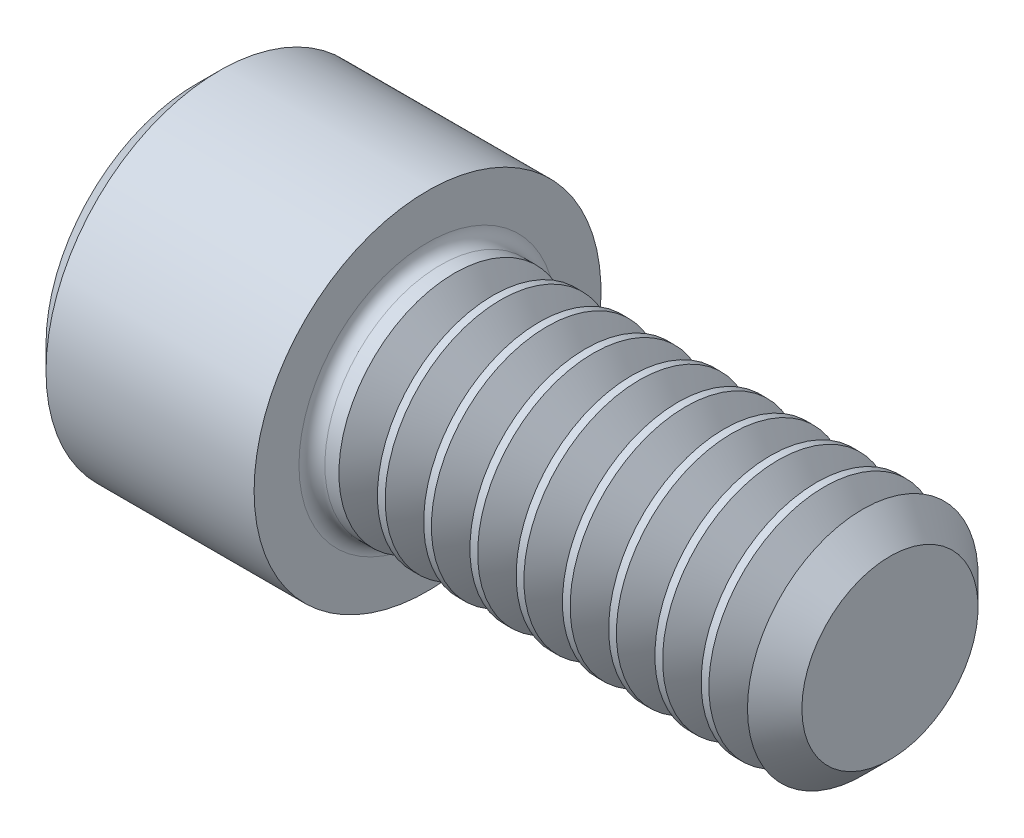
SolidWorks part; units mm, degrees
revolve "Base-Revolve" add sketch "BodySke"
sketch "BodySke" plane through (0, 0, 0) normal (0, 0, 1) x (1, 0, 0)
  line L0 (0, 0) -> (0, 4.1275)
  line L1 (0.635, 4.7625) -> (6.35, 4.7625)
  line L2 (6.35, 4.7625) -> (6.35, 3.175)
  line L3 (6.35, 3.175) -> (18.2944, 3.175)
  line L4 (19.05, 2.4193) -> (19.05, 0)
  line L5 (19.05, 0) -> (0, 0)
  line L6 (-31.75, 0) -> (127, 0) construction
  line L7 (0, 4.1275) -> (0.635, 4.7625)
  line L8 (19.05, 2.4193) -> (18.2944, 3.175)
  line L9 (0, -4.1275) -> (0.635, -4.7625) construction
  line L10 (19.05, -2.4193) -> (18.2944, -3.175) construction
  line L11 (7.62, 9.525) -> (7.62, 3.175) construction
  line L12 (6.35, 9.525) -> (6.35, 3.175) construction
  line L13 (-19.05, 9.525) -> (-19.05, 3.175) construction
  dimension "Diameter" = 6.35
  dimension "Head_ht" = 6.35
  dimension "Length" = 12.7
  dimension "Body_ch_ang" = 45
  dimension "Head_dia" = 9.525
  dimension "Head_ch_ang" = 45
  dimension "Head_side_ht" = 5.715
  dimension "Minor_dia" = 4.8387
  dimension "Advance" = 1.27
  dimension "Thread_nom" = 12.7
  dimension "Thread_length" = 38.1
cosmetic thread "ThreadCosmetic" [suppressed]
fillet "Fillet1" radius 0.3556 1 edges at (6.35, 0, 3.175)
ref_plane "Plane1" through (0, 0, 0) normal (0, 0, 1) x (1, 0, 0)
ref_plane "Plane2" through (0, 0, 0) normal (0, 1, 0) x (1, 0, 0)
ref_plane "Plane3" through (0, 0, 0) normal (1, 0, 0) x (0, 0, -1)
other "Configuration Table"
sketch "Sketch2" plane through (0, 0, 0) normal (0, 0, 1) x (1, 0, 0)
  line L0 (0, 2.3813) -> (3.048, 2.3813)
  line L1 (3.048, 2.3813) -> (4.4228, 0)
  line L2 (-31.75, 0) -> (127, 0) construction
  line L3 (4.4228, 0) -> (0, 0)
  line L4 (0, 0) -> (0, 2.3813)
  line L5 (0, 4.1275) -> (0, -4.1275) construction
  line L6 (0, 0) -> (47.625, 0) construction
  line L7 (6.35, -4.7625) -> (6.35, 4.7625) construction
  dimension "D1" = 2.3813
  dimension "D2" = 60
revolve "Hex-PreBroach" cut sketch "Sketch2" angle 360 about L6
sketch "Sketch3" plane through (0, 0, 0) normal (-1, 0, 0) x (0, 0.5, 0.866)
  line L0 (1.3748, 2.3813) -> (-1.3748, 2.3812)
  line L1 (-1.3748, 2.3812) -> (-2.7496, 0)
  line L2 (1.3748, 2.3813) -> (2.7496, 0)
  line L3 (1.3748, -2.3812) -> (2.7496, 0)
  line L4 (1.3748, -2.3812) -> (-1.3748, -2.3812)
  line L5 (-1.3748, -2.3812) -> (-2.7496, 0)
  dimension "D1" = 2.3813
  dimension "D2" = 2.3813
  dimension "Hex_size" = 4.7625
extrude "Hex" cut sketch "Sketch3" against normal blind 3.048
sketch "Sketch4" plane through (0, 0, 0) normal (-1, 0, 0) x (0, 0, 1)
  line L0 (0, 0) -> (2.8067, 0)
  line L1 (0, 0) -> (6.1484, 3.5498) construction
  line L2 (0, 0) -> (1.4033, 2.4307)
  line L3 (2.3336, 0.614) -> (2.6851, 0.817)
  line L4 (1.6986, 1.7139) -> (2.0501, 1.9169)
  arc A0 (2.3336, 0.614) -> (1.6986, 1.7139) centre (0, 0) ccw
  arc A1 (2.8067, 0) -> (2.6851, 0.817) centre (0, 0) ccw
  arc A2 (1.4033, 2.4307) -> (2.0501, 1.9169) centre (0, 0) cw
  dimension "D2" = 60
  dimension "D1" = 30
  dimension "Spline_p_dim" = 1.27
  dimension "D3" = 0.635
extrude "Spline" [suppressed] cut sketch "Sketch4" against normal blind 3.048
pattern_circular "CirPattern1" [suppressed] count 6 every 60
sketch "Sketch5" plane through (0, 0, 0) normal (0, 0, 1) x (1, 0, 0)
  line L0 (-31.75, 0) -> (127, 0) construction
  line L2 (0, 4.1275) -> (0, -4.1275) construction
  circle A0 centre (2.159, 0) radius 0.5905
  dimension "Drilled_hole_dia" = 1.1811
  dimension "Drilled_hole_loc" = 2.159
extrude "Hole" [suppressed] cut sketch "Sketch5" against normal through all and the other way through all
pattern_circular "Drilled-4" [suppressed] count 2 every 60
pattern_circular "Drilled-6" [suppressed] count 3 every 60
sketch "ThdSchSke" plane through (0, 0, 0) normal (0, 0, 1) x (1, 0, 0)
  line L0 (7.62, -2.4193) -> (7.0909, -3.175)
  line L1 (7.62, -2.4193) -> (8.1491, -3.175)
  line L2 (8.1491, -3.175) -> (8.1491, -3.9688)
  line L3 (-3.175, 0) -> (5.1513, 0) construction
  line L5 (8.1491, -3.9688) -> (7.0909, -3.9688)
  line L6 (7.0909, -3.9688) -> (7.0909, -3.175)
  line L7 (0, 4.1275) -> (0, -4.1275) construction
  dimension "Thread_minor" = 4.8387
  dimension "Diameter" = 6.35
  dimension "Start" = 7.62
revolve "ThreadSchematic" cut sketch "ThdSchSke" angle 360 about L3
pattern_linear "ThdSchPat" count 9 spacing 1.27 along (1, 0, 0) of "ThreadSchematic"
equation "\"D2@Sketch3\" = \"Hex_size@Sketch3\" / 2"
equation "\"D1@Sketch3\" = \"Hex_size@Sketch3\" / 2"
equation "\"D1@Sketch2\" = \"Hex_size@Sketch3\" / 2"
equation "\"D3@Sketch4\" = \"Spline_p_dim@Sketch4\" / 2"
equation "\"Thread_minor@ThreadCosmetic\"  =  \"Minor_dia@BodySke\""
equation "\"D2@CirPattern1\" = 360 / \"Num_teeth@CirPattern1\""
equation "\"Wall_thickness@Sketch2\" = \"Head_ht@BodySke\" - \"Key_eng@Hex\""
equation "\"Thread_length@ThreadCosmetic\" = ((sgn( (\"Length@BodySke\" - \"Advance@BodySke\" ) - \"Thread_nom@BodySke\" )-1)*( (\"Length@BodySke\" - \"Advance@BodySke\" ) - \"Thread_nom@BodySke\" ))/-2+ \"Thread_nom@BodySke\""
equation "\"Thread_minor@ThdSchSke\" = \"Minor_dia@BodySke\""
equation "\"Diameter@ThdSchSke\" = \"Diameter@BodySke\""
equation "\"Overcut@ThdSchSke\" = \"Diameter@BodySke\" * 1.25"
equation "\"Start@ThdSchSke\" = \"Head_ht@BodySke\" + \"Length@BodySke\" - \"Thread_length@ThreadCosmetic\"  '---Non-countersunk---"
equation "\"Num_threads@ThdSchPat\" = int( \"Thread_length@ThreadCosmetic\" / \"Advance@BodySke\" + 0.999 )  + 1"
equation "\"Advance@ThdSchPat\" = \"Thread_length@ThreadCosmetic\" /  (\"Num_threads@ThdSchPat\" - 1) 'relax it"
equation "\"Num_threads@ThdSchPat\" = \"Num_threads@ThdSchPat\" - sgn( \"Num_threads@ThdSchPat\" - 1) '---chamfered tips only---"
